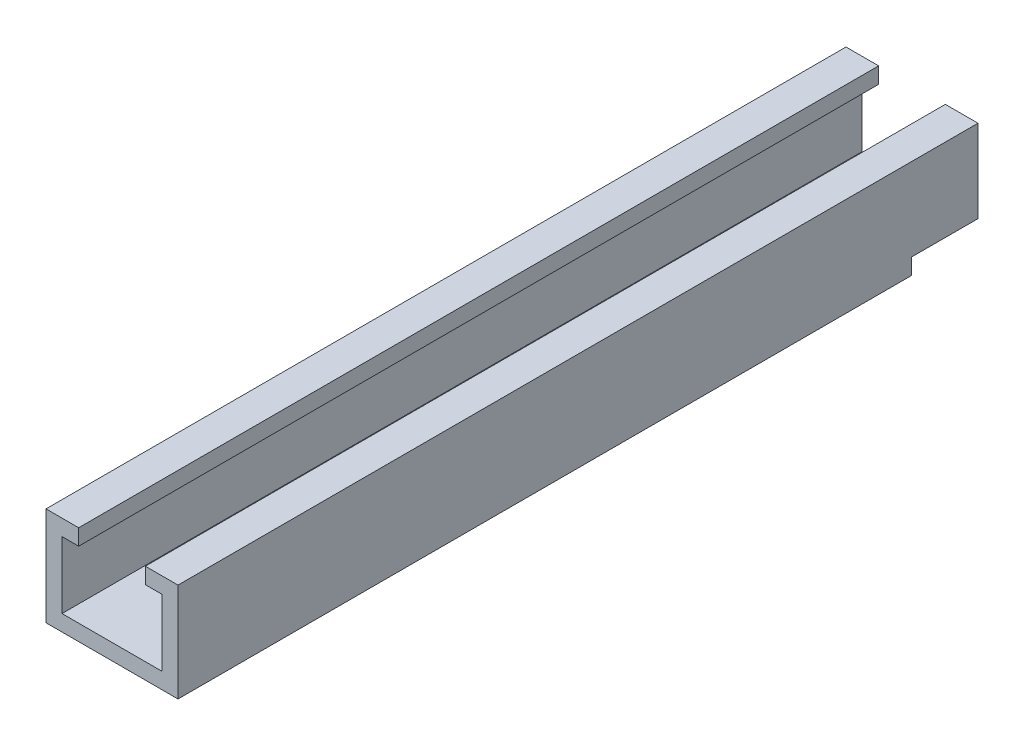
SolidWorks part; units mm, degrees
material "Beech"
ref_plane "Front Plane" through (0, 0, 0) normal (0, 0, 1) x (1, 0, 0)
ref_plane "Top Plane" through (0, 0, 0) normal (0, 1, 0) x (1, 0, 0)
ref_plane "Right Plane" through (0, 0, 0) normal (1, 0, 0) x (0, 0, -1)
sketch "Sketch1" plane through (0, 0, 0) normal (0, 0, 1) x (1, 0, 0)
  line L1 (0, 0) -> (99, 0)
  line L2 (0, 0) -> (0, 12)
  line L3 (0, 12) -> (99, 12)
  line L4 (99, 0) -> (99, 12)
  dimension "D1" = 12
  dimension "D2" = 99
extrude "baseplate" add sketch "Sketch1" along normal blind 600
sketch "Sketch2" plane through (0, 12, 0) normal (0, 1, 0) x (1, 0, 0)
  line L0 (99, -600) -> (0, -600) construction
  line L1 (0, 0) -> (12, 0)
  line L2 (0, 0) -> (0, -600)
  line L3 (0, -600) -> (12, -600)
  line L4 (12, 0) -> (12, -600)
  dimension "D1" = 12
extrude "side_rail" add sketch "Sketch2" along normal blind 50
sketch "Sketch3" plane through (0, 62, 0) normal (0, 1, 0) x (1, 0, 0)
  line L0 (99, -600) -> (12, -600) construction
  line L1 (0, 0) -> (24.5, 0)
  line L2 (0, 0) -> (0, -600)
  line L3 (0, -600) -> (24.5, -600)
  line L4 (24.5, 0) -> (24.5, -600)
  dimension "D1" = 24.5
extrude "keeper rail" add sketch "Sketch3" along normal blind 12
ref_plane "longitudinal midplane" through (49.5, 0, 0) normal (-1, 0, 0) x (0, 0, 1)
mirror "mirror rails" about plane through (49.5, 0, 0) normal (-1, 0, 0) of "keeper rail", "side_rail"
sketch "Sketch5" plane through (0, 0, 0) normal (0, -1, 0) x (1, 0, 0)
  line L0 (99, 600) -> (99, 0) construction
  line L1 (0, 0) -> (99, 0)
  line L2 (0, 0) -> (0, 50)
  line L3 (0, 50) -> (99, 50)
  line L4 (99, 0) -> (99, 50)
  dimension "D1" = 50
extrude "lap joint cutout" cut sketch "Sketch5" against normal blind 12
hole_wizard "lap joint bolt hole pattern" positions "Sketch7" profile "Sketch9" tap size "M5x0.8" standard "ANSI Metric"
sketch "Sketch7" plane through (0, 12, 0) normal (0, -1, 0) x (-1, 0, 0)
  line L1 (-93, -10) -> (-6, -10)
  line L2 (-93, -10) -> (-93, -40)
  line L3 (-93, -40) -> (-6, -40)
  line L4 (-6, -10) -> (-6, -40)
  line L5 (-93, 0) -> (-93, -10)
  line L6 (-87, 0) -> (-99, 0) construction
  line L8 (-6, -10) -> (-6, 0)
  line L9 (0, 0) -> (-12, 0) construction
  line L10 (-6, -25) -> (0, -25)
  line L11 (0, -50) -> (0, 0) construction
  point P1 (-93, -10)
  point P2 (-6, -40)
  point P113 (-93, -40)
  point P114 (-6, -10)
  dimension "D1" = 30
sketch "Sketch9" plane through (93, 12, 10) normal (1, 0, 0) x (0, 0, -1)
  line L0 (0, 0) -> (0, 15.2618)
  line L1 (0, 15.2618) -> (2.1, 14)
  line L2 (2.1, 14) -> (2.1, 0)
  line L5 (2.1, 0) -> (0, 0)
  line L10 (0, 15.2618) -> (-2.1, 14) construction
  line L11 (0, -6.35) -> (0, 107.95) construction
  dimension "Tap Drill Dia." = 4.2
  dimension "Tap Drill Depth" = 14
  dimension "Drill Angle" = 118
cosmetic thread "Hole Thread1" parameters "D1"=10, "D2"=5
cosmetic thread "Hole Thread2" parameters "D1"=10, "D2"=5
cosmetic thread "Hole Thread3" parameters "D1"=10, "D2"=5
cosmetic thread "Hole Thread4" parameters "D1"=10, "D2"=5
equation "\"board_thickness\" = 12mm"
equation "\"way_width\"= 75mm"
equation "\"way_thickness\"= 50mm"
equation "\"radial_clearance\"= 0.1mm"
equation "\"slider_width\"= \"way_width\"-2* \"radial_clearance\""
equation "\"slider_thickness\" = \"way_thickness\" - 2 * \"radial_clearance\""
equation "\"column_width\"= \"way_width\" + 2 * \"board_thickness\""
equation "\"D1@Sketch1\"=\"board_thickness\""
equation "\"D2@Sketch1\"=\"column_width\""
equation "\"D1@Sketch2\"=\"board_thickness\""
equation "\"D1@keeper rail\"=\"board_thickness\""
equation "\"boxway_slot_width\" = 50mm"
equation "\"keeper_rail_width\" = (\"column_width\" - \"boxway_slot_width\")/2"
equation "\"D1@Sketch3\"=\"keeper_rail_width\""
equation "\"slider_length\" = 125mm"
equation "\"nut_diameter\"= 22mm"
equation "\"nut_length\"= 15mm"
equation "\"leadscrew_diameter\"= 10mm"
equation "\"leadscrew_radial_clearance\"= 1mm"
equation "\"bearing_bolt_pattern_width\" = 35mm"
equation "\"bearing_bolt_pattern_height\" = 60mm"
equation "\"desktop_bolt_pattern_width\" = 30mm"
equation "\"desktop_bolt_pattern_height\" = 30mm"
equation "\"bearing_bolt_nut_counterbore_diameter\" = 12mm"
equation "\"bearing_bolt_nut_counterbore_depth\"= 10mm"
equation "\"desktop_depth\"= 500mm"
equation "\"desktop_width\"= 650mm"
equation "\"desktop_thickness\"= 15mm"
equation "\"leg_height\"=75mm"
equation "\"leg_width\"=12mm"
equation "\"leg_length\"=500mm"
equation "\"D1@lap joint cutout\" = \"leg_width\""
equation "\"lap_joint_height\" = 50mm"
equation "\"lap_dowel_diameter\"= 8mm"
equation "\"lap_dowel_hole_z_spacing\"=30"
equation "\"D1@Sketch5\"=\"lap_joint_height\""
equation "\"D1@Sketch7\"=\"lap_dowel_hole_z_spacing\""
